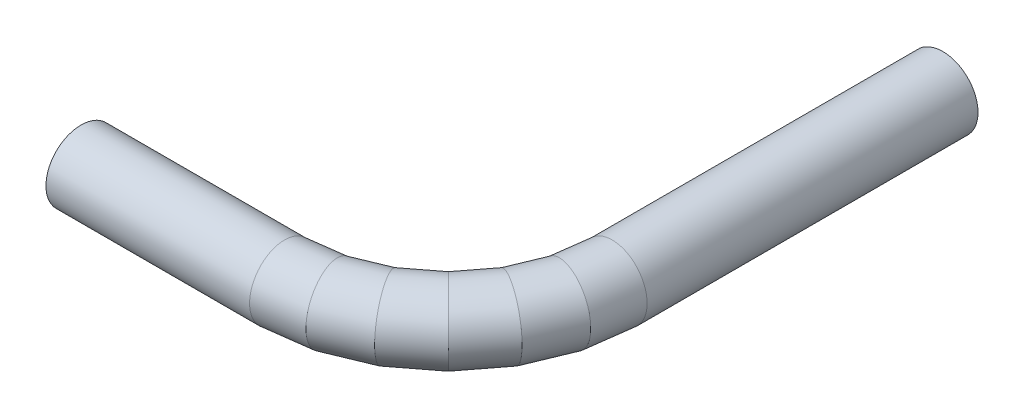
SolidWorks part; units mm, degrees
ref_plane "Front Plane" through (0, 0, 0) normal (0, 0, 1) x (1, 0, 0)
ref_plane "Top Plane" through (0, 0, 0) normal (0, 1, 0) x (1, 0, 0)
ref_plane "Right Plane" through (0, 0, 0) normal (1, 0, 0) x (0, 0, -1)
sketch3d "Path"
  line L0 (-2944.7928, 0, 70) -> (-2926.5928, 0, 70)
  line L1 (-2926.5928, 0, 70) -> (-2922.7105, 0, 69.4889)
  line L2 (-2922.7105, 0, 69.4889) -> (-2919.0928, 0, 67.9904)
  line L3 (-2919.0928, 0, 67.9904) -> (-2915.9862, 0, 65.6066)
  line L4 (-2915.9862, 0, 65.6066) -> (-2913.6024, 0, 62.5)
  line L5 (-2913.6024, 0, 62.5) -> (-2912.1039, 0, 58.8823)
  line L6 (-2912.1039, 0, 58.8823) -> (-2911.5928, 0, 55)
  line L7 (-2911.5928, 0, 55) -> (-2911.5928, 0, 25.3)
ref_plane "Start Plane" through (-2944.7928, 0, 0) normal (1, 0, 0) x (0, 0, -1)
sketch "Profile" plane through (-2944.7928, 0, 0) normal (1, 0, 0) x (0, 0, -1)
  circle A0 centre (-70, 0) radius 3.175
  circle A1 centre (-70, 0) radius 2.286
sweep "Tube" add profiles "Profile" path "Path"
